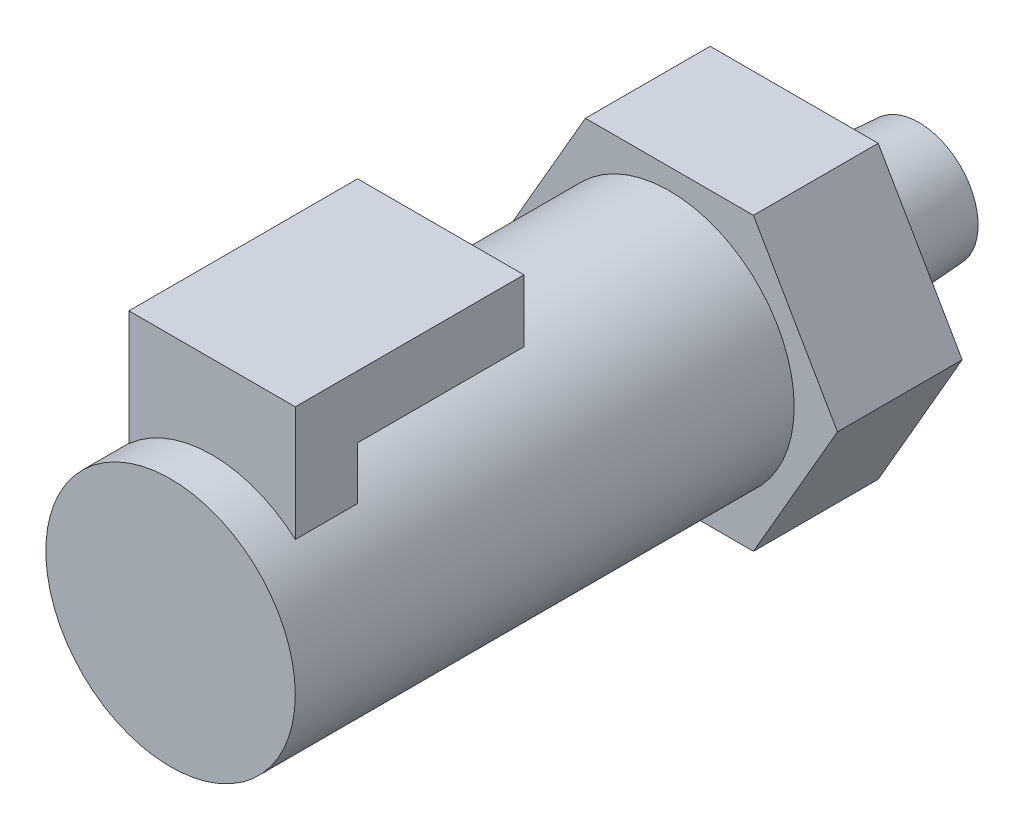
SolidWorks part; units mm, degrees
ref_plane "Front Plane" through (0, 0, 0) normal (0, 0, 1) x (1, 0, 0)
ref_plane "Top Plane" through (0, 0, 0) normal (0, 1, 0) x (1, 0, 0)
ref_plane "Right Plane" through (0, 0, 0) normal (1, 0, 0) x (0, 0, -1)
sketch "Sketch1" plane through (0, 0, 0) normal (0, 0, 1) x (1, 0, 0)
  line L1 (6.4158, 11.1125) -> (-6.4158, 11.1125)
  line L2 (-6.4158, 11.1125) -> (-12.8316, 0)
  line L3 (-12.8316, 0) -> (-6.4158, -11.1125)
  line L4 (-6.4158, -11.1125) -> (6.4158, -11.1125)
  line L5 (6.4158, -11.1125) -> (12.8316, 0)
  line L6 (12.8316, 0) -> (6.4158, 11.1125)
  circle A0 centre (0, 0) radius 11.1125 construction
  dimension "D1" = 22.225
extrude "Boss-Extrude1" add sketch "Sketch1" along normal blind 9.525
sketch "Sketch2" plane through (0, 0, 0) normal (0, 0, -1) x (-1, 0, 0)
  circle A0 centre (0, 0) radius 5.1054
  dimension "D1" = 10.2108
extrude "Boss-Extrude2" add sketch "Sketch2" along normal blind 9.525 draft 3.5
sketch "Sketch3" plane through (0, 0, 9.525) normal (0, 0, 1) x (1, 0, 0)
  circle A0 centre (0, 0) radius 9.525
  dimension "D1" = 19.05
extrude "Boss-Extrude3" add sketch "Sketch3" along normal blind 38.1
ref_plane "Plane1" through (0, 9.525, 0) normal (0, 1, 0) x (1, 0, 0)
sketch "Sketch5" plane through (0, 9.525, 0) normal (0, 1, 0) x (1, 0, 0)
  line L1 (-6.35, -44.45) -> (6.35, -44.45)
  line L2 (-6.35, -44.45) -> (-6.35, -39.6875)
  line L3 (-6.35, -39.6875) -> (6.35, -39.6875)
  line L4 (6.35, -44.45) -> (6.35, -39.6875)
  line L5 (0, -9.525) -> (0, -47.625)
  line L6 (0, -9.525) -> (0, -47.625) construction
  line L7 (-9.525, -47.625) -> (9.525, -47.625) construction
  dimension "D1" = 6.35
  dimension "D2" = 6.35
  dimension "D3" = 3.175
  dimension "D4" = 4.7625
extrude "Boss-Extrude5" add sketch "Sketch5" along normal blind 6.35 and the other way blind 9.525
sketch "Sketch6" plane through (0, 0, 39.6875) normal (0, 0, -1) x (-1, 0, 0)
  line L0 (6.35, 7.0995) -> (6.35, 15.875) construction
  line L1 (-6.35, 15.875) -> (6.35, 15.875)
  line L2 (-6.35, 15.875) -> (-6.35, 11.1125)
  line L3 (-6.35, 11.1125) -> (6.35, 11.1125)
  line L4 (6.35, 15.875) -> (6.35, 11.1125)
  dimension "D1" = 4.7625
extrude "Boss-Extrude6" add sketch "Sketch6" along normal blind 12.7
